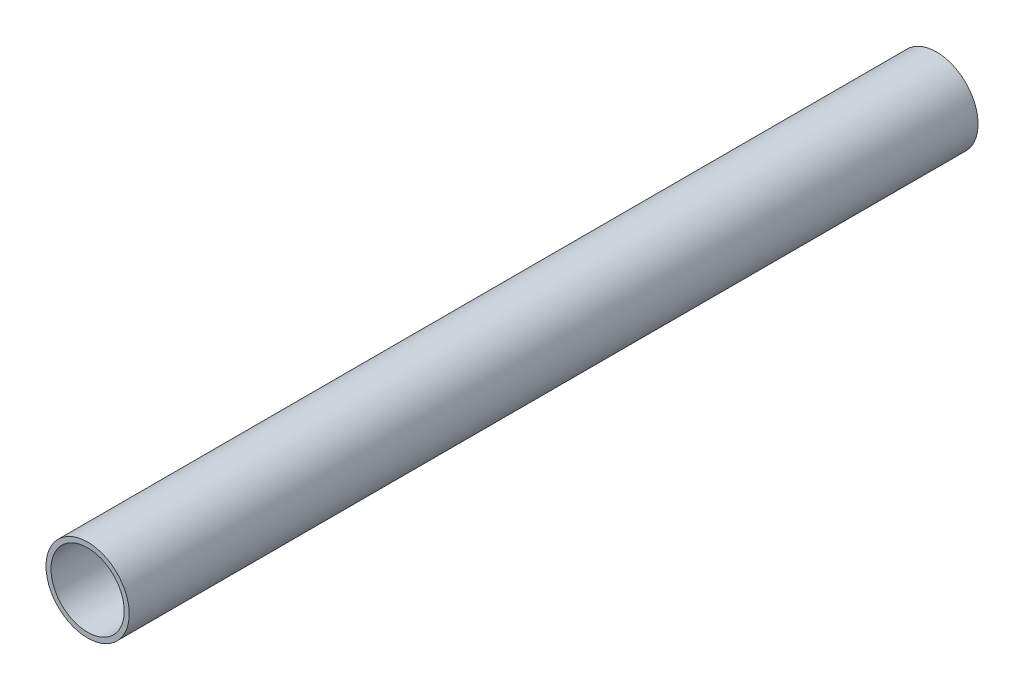
SolidWorks part; units mm, degrees
ref_plane "前视基准面" through (0, 0, 0) normal (0, 0, 1) x (1, 0, 0)
ref_plane "上视基准面" through (0, 0, 0) normal (0, 1, 0) x (1, 0, 0)
ref_plane "右视基准面" through (0, 0, 0) normal (1, 0, 0) x (0, 0, -1)
sketch "草图1" plane through (0, 0, 0) normal (0, 0, 1) x (1, 0, 0)
  circle A0 centre (0, 0) radius 12.5
extrude "凸台-拉伸2" add sketch "草图1" along normal blind 235.43 contours A0
sketch "草图2" plane through (0, 0, 0) normal (0, 0, -1) x (-1, 0, 0)
  circle A0 centre (0, 0) radius 9
extrude "切除-拉伸1" cut sketch "草图2" against normal blind 235.43
sketch "草图3" plane through (0, 0, 0) normal (0, 0, -1) x (-1, 0, 0)
  circle A0 centre (0, 0) radius 12.5
extrude "凸台-拉伸3" add sketch "草图3" along normal blind 15.57
sketch "草图4" plane through (0, 0, -15.57) normal (0, 0, -1) x (-1, 0, 0)
  circle A0 centre (0, 0) radius 9
extrude "切除-拉伸2" cut sketch "草图4" against normal blind 20
sketch "草图5" plane through (0, 0, -15.57) normal (0, 0, -1) x (-1, 0, 0)
  circle A0 centre (0, 0) radius 12.5
extrude "凸台-拉伸4" add sketch "草图5" along normal blind 9.93
sketch "草图6" plane through (0, 0, -25.5) normal (0, 0, -1) x (-1, 0, 0)
  circle A0 centre (0, 0) radius 9
extrude "切除-拉伸3" cut sketch "草图6" against normal blind 10
sketch "草图7" plane through (0, 0, -25.5) normal (0, 0, -1) x (-1, 0, 0)
  circle A0 centre (0, 0) radius 26.8585
extrude "切除-拉伸4" cut sketch "草图7" against normal blind 14.93
sketch "草图8" plane through (0, 0, -10.57) normal (0, 0, -1) x (-1, 0, 0)
  circle A0 centre (0, 0) radius 12.5
extrude "凸台-拉伸5" add sketch "草图8" along normal blind 9.93
sketch "草图9" plane through (0, 0, -20.5) normal (0, 0, -1) x (-1, 0, 0)
  circle A0 centre (0, 0) radius 9
extrude "切除-拉伸5" cut sketch "草图9" against normal blind 10
sketch "草图10" plane through (0, 0, -20.5) normal (0, 0, -1) x (-1, 0, 0)
  circle A0 centre (7.2017, 7.5079) radius 37.1934
extrude "切除-拉伸6" cut sketch "草图10" against normal blind 0.22
sketch "草图11" plane through (0, 0, -20.28) normal (0, 0, -1) x (-1, 0, 0)
  circle A0 centre (-1.2255, 2.3294) radius 43.1872
extrude "切除-拉伸7" cut sketch "草图11" against normal blind 0.71
sketch "草图12" plane through (0, 0, -19.57) normal (0, 0, -1) x (-1, 0, 0)
  circle A0 centre (0, 0) radius 11
extrude "切除-拉伸8" cut sketch "草图12" against normal blind 338
